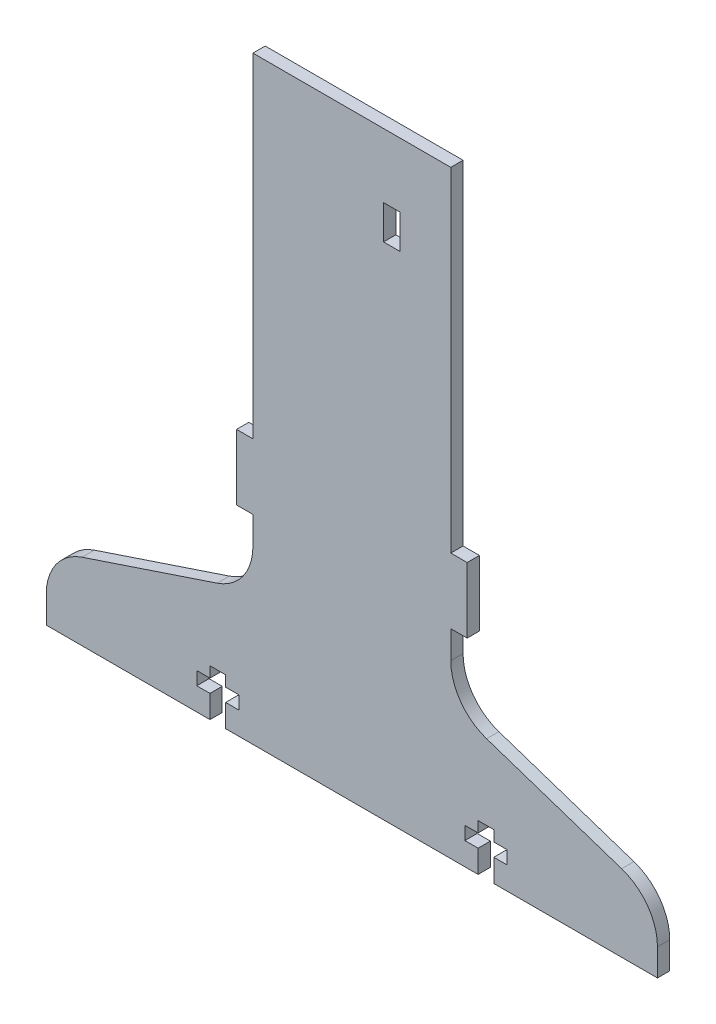
SolidWorks part; units mm, degrees
ref_plane "Front Plane" through (0, 0, 0) normal (0, 0, 1) x (1, 0, 0)
ref_plane "Top Plane" through (0, 0, 0) normal (0, 1, 0) x (1, 0, 0)
ref_plane "Right Plane" through (0, 0, 0) normal (1, 0, 0) x (0, 0, -1)
sketch "Sketch1" plane through (0, 0, 0) normal (0, 0, 1) x (1, 0, 0)
  line L1 (-7.9375, 0) -> (7.9375, 0)
  line L2 (-7.9375, 0) -> (-7.9375, 83.8378)
  line L3 (-7.9375, 83.8378) -> (7.9375, 83.8378)
  line L4 (7.9375, 0) -> (7.9375, 83.8378)
  line L5 (-2.8575, 71.3918) -> (0.3175, 71.3918)
  line L6 (-2.8575, 71.3918) -> (-2.8575, 64.7878)
  line L7 (-2.8575, 64.7878) -> (0.3175, 64.7878)
  line L8 (0.3175, 71.3918) -> (0.3175, 64.7878)
  dimension "D1" = 83.8378
  dimension "D2" = 3.175
  dimension "D3" = 7.62
  dimension "D4" = 6.604
  dimension "D6" = 15.875
  dimension "D7" = 12.446
extrude "Boss-Extrude1" add sketch "Sketch1" along normal blind 2.3813
sketch "Sketch2" plane through (0, 0, 0) normal (0, 0, 1) x (1, 0, 0)
  line L1 (7.9375, 0) -> (13.3642, 0)
  line L2 (7.9375, 0) -> (7.9375, 83.8378)
  line L3 (7.9375, 83.8378) -> (13.3642, 83.8378)
  line L4 (13.3642, 0) -> (13.3642, 83.8378)
  line L5 (-7.9375, 83.8378) -> (-31.3619, 83.8378)
  line L6 (-7.9375, 83.8378) -> (-7.9375, 0)
  line L7 (-7.9375, 0) -> (-31.3619, 0)
  line L8 (-31.3619, 83.8378) -> (-31.3619, 0)
  dimension "D1" = 5.4267
  dimension "D2" = 23.4244
extrude "Boss-Extrude2" add sketch "Sketch2" along normal blind 2.3813
sketch "Sketch3" plane through (0, 0, 0) normal (0, 0, 1) x (1, 0, 0)
  line L0 (13.3642, 0) -> (13.3642, 83.8378) construction
  line L1 (-31.3619, 83.8378) -> (-28.1869, 83.8378)
  line L2 (-31.3619, 83.8378) -> (-31.3619, 19.05)
  line L3 (-31.3619, 19.05) -> (-28.1869, 19.05)
  line L4 (-28.1869, 83.8378) -> (-28.1869, 19.05)
  line L5 (13.3642, 19.05) -> (10.1892, 19.05)
  line L6 (13.3642, 19.05) -> (13.3642, 83.8378)
  line L7 (13.3642, 83.8378) -> (10.1892, 83.8378)
  line L8 (10.1892, 19.05) -> (10.1892, 83.8378)
  line L9 (13.3642, 83.8378) -> (-31.3619, 83.8378) construction
  line L10 (-31.3619, 0) -> (13.3642, 0) construction
  line L12 (-31.3619, 0) -> (-28.1869, 0)
  line L13 (-31.3619, 0) -> (-31.3619, 6.35)
  line L14 (-31.3619, 6.35) -> (-28.1869, 6.35)
  line L15 (-28.1869, 0) -> (-28.1869, 6.35)
  line L16 (13.3642, 0) -> (10.1892, 0)
  line L17 (13.3642, 0) -> (13.3642, 6.35)
  line L18 (13.3642, 6.35) -> (10.1892, 6.35)
  line L19 (10.1892, 0) -> (10.1892, 6.35)
  dimension "D1" = 19.05
  dimension "D2" = 3.175
  dimension "D3" = 6.35
extrude "Cut-Extrude2" cut sketch "Sketch3" along normal through all
sketch "Sketch4" plane through (0, 0, 2.3813) normal (0, 0, 1) x (1, 0, 0)
  line L0 (-12.9946, 19.0693) -> (-12.9946, 38.2214) construction
  line L1 (-20.6339, 19.0693) -> (-20.6339, 38.2214)
  line L2 (-5.3553, 19.0693) -> (-5.3553, 38.2214)
  arc A0 (-20.6339, 19.0693) -> (-5.3553, 19.0693) centre (-12.9946, 19.0693) ccw
  arc A1 (-5.3553, 38.2214) -> (-20.6339, 38.2214) centre (-12.9946, 38.2214) ccw
  point P2 (-12.9946, 28.6453)
extrude "Cut-Extrude3" [suppressed] cut sketch "Sketch4" against normal through all
sketch "Sketch5" plane through (0, 0, 0) normal (0, 0, 1) x (1, 0, 0)
  line L0 (-28.1869, 0) -> (-28.1869, -6.35)
  line L1 (-28.1869, -6.35) -> (-68.268, -19.7171)
  line L2 (-68.268, -19.7171) -> (-68.268, -32.2821)
  line L3 (-68.268, -32.2821) -> (50.2703, -32.2821)
  line L4 (50.2703, -32.2821) -> (50.2703, -19.7171)
  line L5 (50.2703, -19.7171) -> (10.1892, -6.35)
  line L6 (10.1892, -6.35) -> (10.1892, 0)
  line L7 (-28.1869, 0) -> (10.1892, 0)
  line L8 (-28.1869, 0) -> (-28.1869, 6.35) construction
  line L9 (-28.1869, 0) -> (10.1892, 0) construction
  line L10 (-28.1869, 0) -> (10.1892, 0) construction
  dimension "D1" = 12.5649
  dimension "D2" = 13.3671
  dimension "D3" = 6.35
extrude "Boss-Extrude4" add sketch "Sketch5" along normal blind 2.3813
fillet "Fillet1" radius 10.16 4 edges at (10.1892, -6.35, 1.1906) (-28.1869, -6.35, 1.1906) (50.2703, -19.7171, 1.1906) (-68.268, -19.7171, 1.1906)
sketch "Sketch6" plane through (0, 0, 0) normal (0, 0, 1) x (1, 0, 0)
  line L0 (-68.268, -32.2821) -> (50.2703, -32.2821) construction
  line L2 (50.2703, -32.2821) -> (50.2703, -27.0389) construction
  point P0 (50.2703, -29.6605)
  line B0 (-36.518, -32.2821) -> (-36.518, -27.8707)
  line B1 (-36.518, -27.8707) -> (-39.0765, -27.8707)
  line B2 (-39.0765, -27.8707) -> (-39.0765, -25.3122)
  line B3 (-39.0765, -25.3122) -> (-36.518, -25.3122)
  line B4 (-36.518, -25.3122) -> (-36.518, -23.2334)
  line B5 (-36.518, -23.2334) -> (-33.4798, -23.2334)
  line B6 (-33.4798, -23.2334) -> (-33.4798, -25.3122)
  line B7 (-33.4798, -25.3122) -> (-30.9213, -25.3122)
  line B8 (-30.9213, -25.3122) -> (-30.9213, -27.8707)
  line B9 (-30.9213, -27.8707) -> (-33.4798, -27.8707)
  line B10 (-33.4798, -27.8707) -> (-33.4798, -32.2821)
  line B11 (-33.4798, -32.2821) -> (-36.518, -32.2821)
  line B12 (15.4821, -32.2821) -> (15.4821, -27.8707)
  line B13 (15.4821, -27.8707) -> (12.9236, -27.8707)
  line B14 (12.9236, -27.8707) -> (12.9236, -25.3122)
  line B15 (12.9236, -25.3122) -> (15.4821, -25.3122)
  line B16 (15.4821, -25.3122) -> (15.4821, -23.2334)
  line B17 (15.4821, -23.2334) -> (18.5203, -23.2334)
  line B18 (18.5203, -23.2334) -> (18.5203, -25.3122)
  line B19 (18.5203, -25.3122) -> (21.0788, -25.3122)
  line B20 (21.0788, -25.3122) -> (21.0788, -27.8707)
  line B21 (21.0788, -27.8707) -> (18.5203, -27.8707)
  line B22 (18.5203, -27.8707) -> (18.5203, -32.2821)
  line B23 (18.5203, -32.2821) -> (15.4821, -32.2821)
  dimension "D1" = 31.75
  dimension "D2" = 31.75
sketch_block_instance "Block1-1"
sketch_block "Block1"
sketch_block_instance "Block1-2"
extrude "Cut-Extrude5" cut sketch "Sketch6" along normal through all
